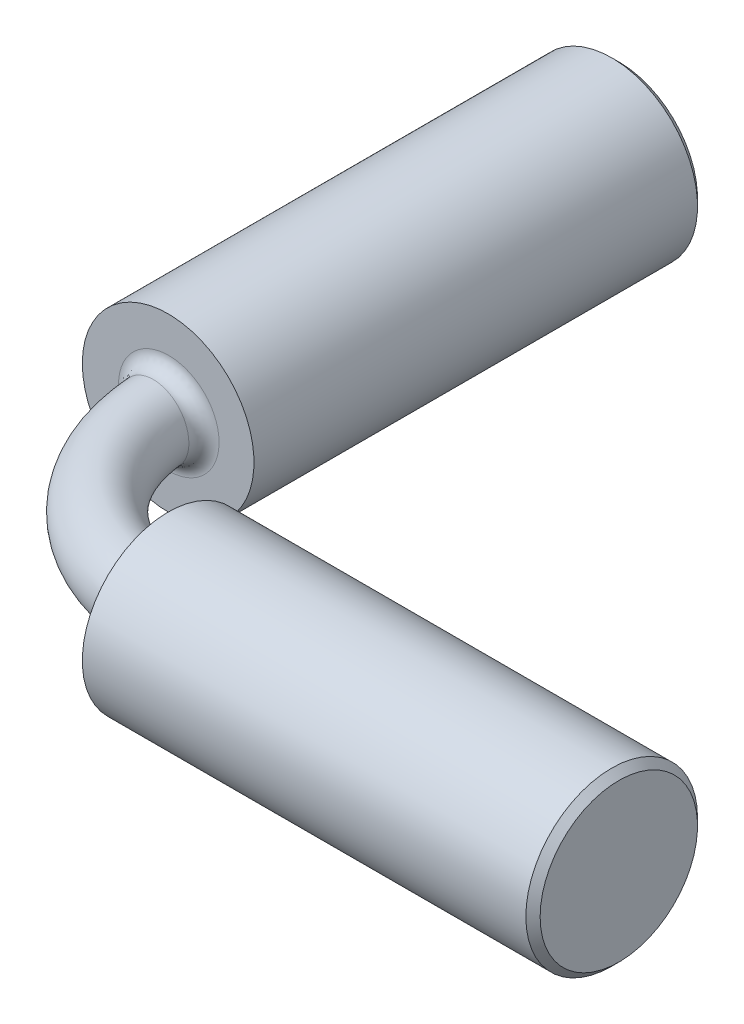
SolidWorks part; units mm, degrees
ref_plane "Front Plane" through (0, 0, 0) normal (0, 0, 1) x (1, 0, 0)
ref_plane "Top Plane" through (0, 0, 0) normal (0, 1, 0) x (1, 0, 0)
ref_plane "Right Plane" through (0, 0, 0) normal (1, 0, 0) x (0, 0, -1)
sketch "Sketch1" plane through (0, 0, 0) normal (0, 1, 0) x (1, 0, 0)
  line L0 (0, 31.5) -> (0, 0)
  line L1 (12, -12) -> (43.5, -12)
  arc A0 (0, 0) -> (12, -12) centre (12, 0) ccw
  dimension "D3" = 12
  dimension "D1" = 31.5
  dimension "D2" = 31.5
sweep "Sweep2" add path "Sketch1" circular profile diameter 5 parameters "D3"=5
sketch "Sketch49" plane through (43.5, 0, 0) normal (1, 0, 0) x (0, 0, -1)
  circle A0 centre (-12, 0) radius 6
extrude "Boss-Extrude9" add sketch "Sketch49" against normal blind 31.5 contours A0
sketch "Sketch54" plane through (0, 0, -31.5) normal (0, 0, -1) x (-1, 0, 0)
  circle A0 centre (0, 0) radius 6
extrude "Boss-Extrude10" add sketch "Sketch54" against normal blind 31.5
fillet "Fillet32" radius 1 1 edges at (12, 0, 9.5)
fillet "Fillet33" radius 1 1 edges at (-2.5, 0, 0)
chamfer "Chamfer1" distance 0.5 angle 45 1 edges at (43.5, 0, 6)
chamfer "Chamfer2" distance 0.5 angle 45 1 edges at (-6, 0, -31.5)
